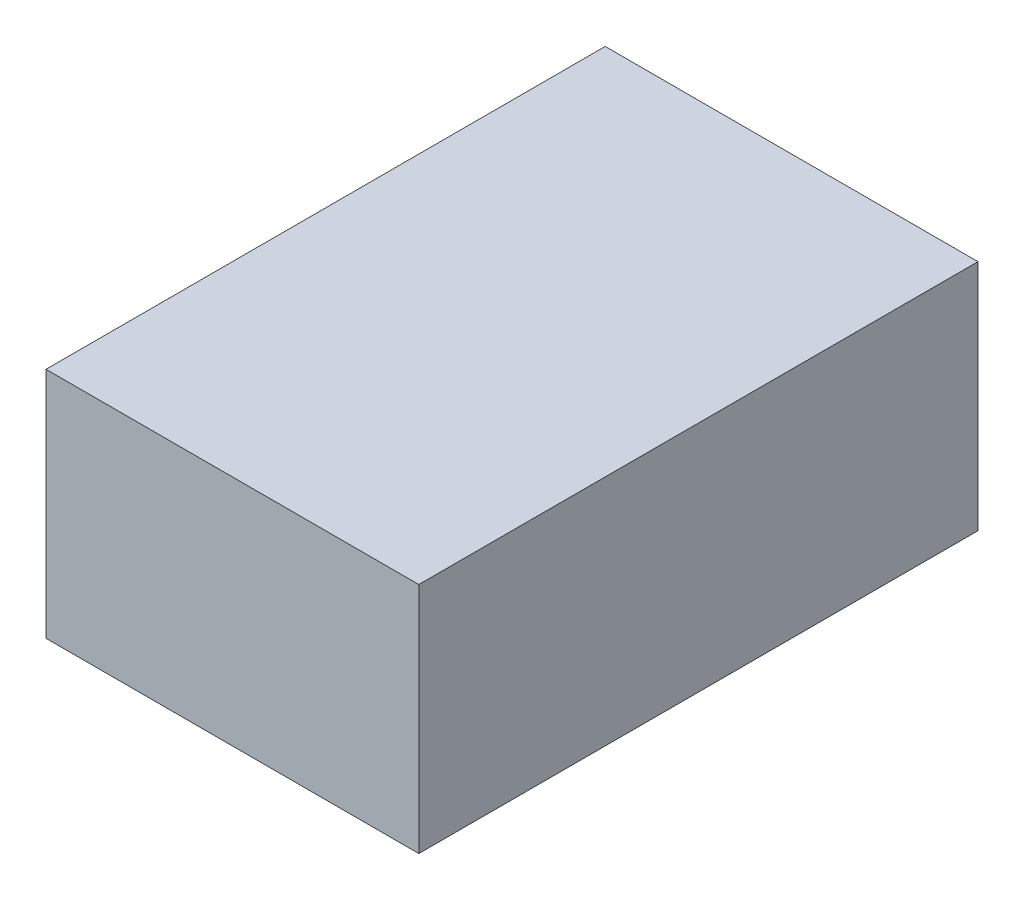
SolidWorks part; units mm, degrees
ref_plane "Front Plane" through (0, 0, 0) normal (0, 0, 1) x (1, 0, 0)
ref_plane "Top Plane" through (0, 0, 0) normal (0, 1, 0) x (1, 0, 0)
ref_plane "Right Plane" through (0, 0, 0) normal (1, 0, 0) x (0, 0, -1)
sketch "Sketch1" plane through (0, 0, 0) normal (0, 0, 1) x (1, 0, 0)
  line L1 (101.6, -63.5) -> (-101.6, -63.5)
  line L2 (101.6, -63.5) -> (101.6, 63.5)
  line L3 (101.6, 63.5) -> (-101.6, 63.5)
  line L4 (-101.6, -63.5) -> (-101.6, 63.5)
  line L5 (101.6, -63.5) -> (-101.6, 63.5) construction
  line L6 (101.6, 63.5) -> (-101.6, -63.5) construction
  point P0 (0, 0)
  dimension "D1" = 127
  dimension "D2" = 203.2
extrude "Boss-Extrude1" add sketch "Sketch1" along normal blind 304.8
